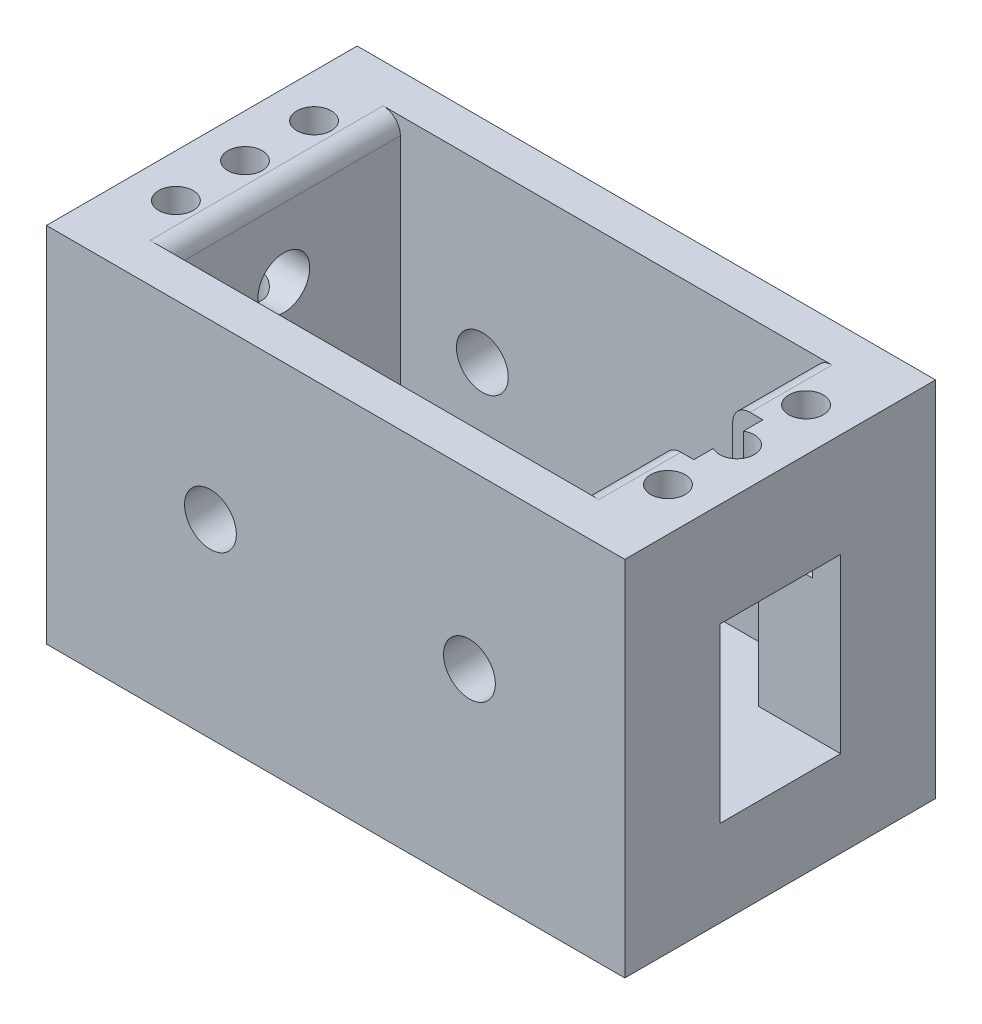
SolidWorks part; units mm, degrees
material "PET"
ref_plane "Alzado" through (0, 0, 0) normal (0, 0, 1) x (1, 0, 0)
ref_plane "Planta" through (0, 0, 0) normal (0, 1, 0) x (1, 0, 0)
ref_plane "Vista lateral" through (0, 0, 0) normal (1, 0, 0) x (0, 0, -1)
sketch "Croquis1" plane through (0, 0, 0) normal (0, 1, 0) x (1, 0, 0)
  line L1 (-16.75, -9) -> (16.75, -9)
  line L2 (-16.75, -9) -> (-16.75, 9)
  line L3 (-16.75, 9) -> (16.75, 9)
  line L4 (16.75, -9) -> (16.75, 9)
  line L5 (-16.75, -9) -> (16.75, 9) construction
  line L6 (-16.75, 9) -> (16.75, -9) construction
  point P0 (0, 0)
  dimension "D1" = 33.5
  dimension "D2" = 18
extrude "Saliente-Extruir1" add sketch "Croquis1" along normal blind 21
sketch "Croquis2" plane through (0, 21, 0) normal (0, 1, 0) x (1, 0, 0)
  line L1 (-11.75, -6.75) -> (11.75, -6.75)
  line L2 (-11.75, -6.75) -> (-11.75, 6.75)
  line L3 (-11.75, 6.75) -> (11.75, 6.75)
  line L4 (11.75, -6.75) -> (11.75, 6.75)
  line L5 (-11.75, -6.75) -> (11.75, 6.75) construction
  line L6 (-11.75, 6.75) -> (11.75, -6.75) construction
  point P0 (0, 0)
  dimension "D1" = 23.5
  dimension "D2" = 13.5
extrude "Cortar-Extruir1" cut sketch "Croquis2" against normal blind 16 contours L2 L1 L4 L3
sketch "Croquis3" plane through (11.75, 0, 0) normal (-1, 0, 0) x (0, 0, 1)
  line L0 (6.75, 5) -> (-6.75, 5) construction
  line L1 (-3.5, 5) -> (3.5, 5)
  line L2 (-3.5, 5) -> (-3.5, 15)
  line L3 (-3.5, 15) -> (3.5, 15)
  line L4 (3.5, 5) -> (3.5, 15)
  point P6 (0, 5)
  point P7 (0, 5)
  dimension "D1" = 10
  dimension "D2" = 7
extrude "Cortar-Extruir2" cut sketch "Croquis3" against normal up to next
sketch "Croquis4" plane through (0, 21, 0) normal (0, 1, 0) x (1, 0, 0)
  line L0 (11.75, 0) -> (16.75, 0) construction
  line L1 (11.75, -6.75) -> (11.75, 6.75) construction
  line L2 (16.75, -9) -> (16.75, 9) construction
  line L3 (-11.55, 0) -> (11.55, 0) construction
  line L4 (0, -9.9) -> (0, 9.9) construction
  circle A0 centre (14.25, 0) radius 1
  circle A1 centre (14.25, 4) radius 1
  circle A2 centre (14.25, -4) radius 1
  circle A3 centre (-14.25, -4) radius 1
  circle A4 centre (-14.25, 0) radius 1
  circle A5 centre (-14.25, 4) radius 1
  dimension "D1" = 2
  dimension "D2" = 4
extrude "Cortar-Extruir3" cut sketch "Croquis4" against normal blind 8
sketch "Croquis5" plane through (0, 21, 0) normal (0, 1, 0) x (1, 0, 0)
  line L0 (11.75, -6.75) -> (11.75, 6.75) construction
  line L1 (11.75, -2) -> (13.75, -2)
  line L2 (11.75, -2) -> (11.75, 2)
  line L3 (11.75, 2) -> (13.75, 2)
  line L4 (13.75, -2) -> (13.75, 2)
  point P6 (11.75, 0)
  point P7 (11.75, 0)
  dimension "D1" = 2
  dimension "D2" = 4
extrude "Cortar-Extruir4" cut sketch "Croquis5" against normal up to next
sketch "Croquis6" plane through (0, 5, 0) normal (0, 1, 0) x (1, 0, 0)
  line L0 (11.75, 2) -> (11.75, 6.75) construction
  circle A0 centre (4.75, 0) radius 1.5
  dimension "D2" = 3
  dimension "D1" = 7
extrude "Cortar-Extruir5" cut sketch "Croquis6" against normal up to next
sketch "Croquis7" plane through (-16.75, 0, 0) normal (-1, 0, 0) x (0, 0, 1)
  line L0 (-9, 21) -> (9, 21) construction
  circle A0 centre (0, 16) radius 1.5
  circle A1 centre (0, 9) radius 1.5
  dimension "D3" = 3
  dimension "D1" = 5
  dimension "D2" = 7
extrude "Cortar-Extruir6" cut sketch "Croquis7" against normal up to next
sketch "Croquis8" plane through (0, 0, -9) normal (0, 0, -1) x (-1, 0, 0)
  line L0 (-16.75, 21) -> (16.75, 21) construction
  line L1 (-16.75, 21) -> (-16.75, 0) construction
  circle A0 centre (-7.75, 11) radius 1.5
  circle A1 centre (7.25, 11) radius 1.5
  dimension "D1" = 3
  dimension "D2" = 10
  dimension "D3" = 9
  dimension "D4" = 15
extrude "Cortar-Extruir7" cut sketch "Croquis8" against normal through all
sketch "Croquis9" plane through (0, 21, 0) normal (0, 1, 0) x (1, 0, 0)
  line L0 (0, -9.9) -> (0, 9.9) construction
  line L1 (-11.75, 6.75) -> (-12, 6.75)
  line L2 (-11.75, 6.75) -> (-11.75, -6.75)
  line L3 (-11.75, -6.75) -> (-12, -6.75)
  line L4 (-12, 6.75) -> (-12, -6.75)
  line L5 (11.75, -6.75) -> (12, -6.75)
  line L6 (12, 6.75) -> (12, -6.75)
  line L7 (11.75, 6.75) -> (12, 6.75)
  line L8 (11.75, 6.75) -> (11.75, -6.75)
  dimension "D1" = 0.25
extrude "Cortar-Extruir8" cut sketch "Croquis9" against normal up to surface (16 mm away) up to face at (4.75, 5, 1.5)
fillet "Redondeo1" radius 1 3 edges at (12, 21, 4.375) (12, 21, -4.375) (-12, 21, 0)
equation "\"A\"= 23.5mm"
equation "\"B\"= 13.5mm"
equation "\"C\"= 16mm"
equation "\"D1@Croquis1\"=\"A\"+10"
equation "\"D2@Croquis1\"=\"B\"+4.50"
